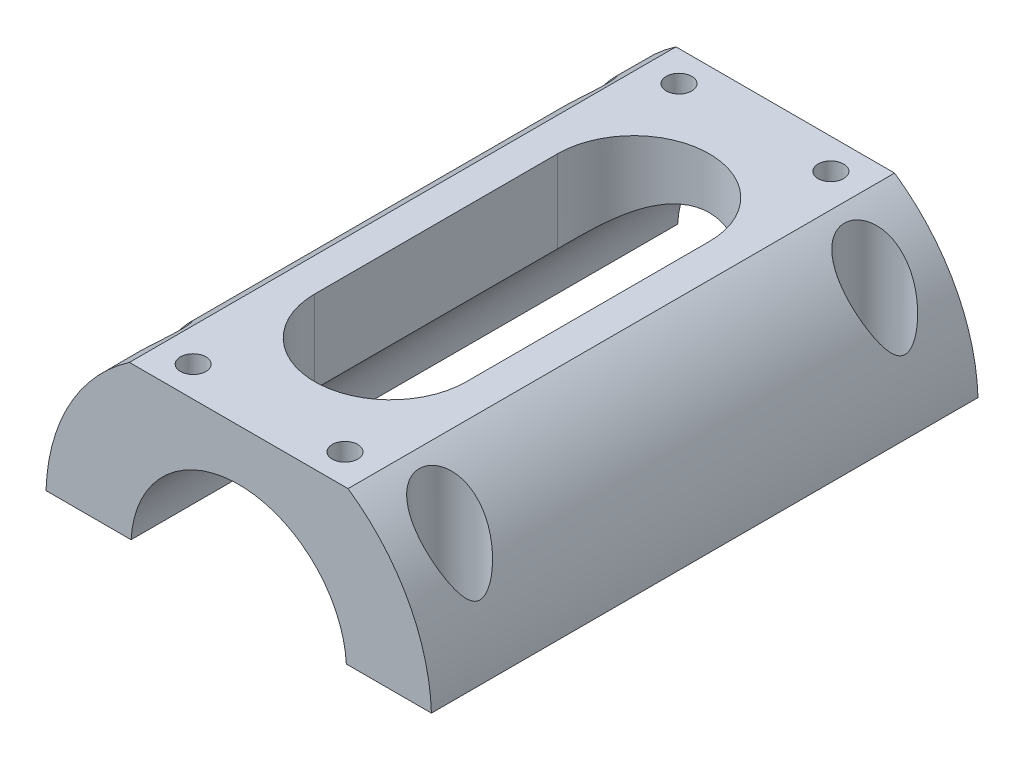
SolidWorks part; units mm, degrees
ref_plane "Front" through (0, 0, 0) normal (0, 0, 1) x (1, 0, 0)
ref_plane "Top" through (0, 0, 0) normal (0, 1, 0) x (1, 0, 0)
ref_plane "Right" through (0, 0, 0) normal (1, 0, 0) x (0, 0, -1)
sketch "Sketch1" plane through (0, 0, 0) normal (0, 0, 1) x (1, 0, 0)
  line L0 (-31.75, 0) -> (31.75, 0) construction
  line L1 (-31.7342, 1) -> (-17.7218, 1)
  line L2 (-31.75, 1) -> (31.75, 1) construction
  line L3 (17.7218, 1) -> (31.7342, 1)
  arc A0 (31.7342, 1) -> (-31.7342, 1) centre (0, 0) ccw
  arc A1 (17.7218, 1) -> (-17.7218, 1) centre (0, 0) ccw
  dimension "D1" = 35.5
  dimension "D2" = 63.5
  dimension "D3" = 1
extrude "Boss-Extrude1" add sketch "Sketch1" along normal blind 90
sketch "Sketch2" plane through (0, 1, 0) normal (0, -1, 0) x (-1, 0, 0)
  line L0 (24.728, -90) -> (24.728, 0) construction
  line L1 (31.7342, -90) -> (17.7218, -90) construction
  line L2 (31.7342, 0) -> (17.7218, 0) construction
  line L3 (-24.728, -90) -> (-24.728, 0) construction
  line L4 (-17.7218, -90) -> (-31.7342, -90) construction
  line L5 (-17.7218, 0) -> (-31.7342, 0) construction
  line L6 (0, -90) -> (0, 0) construction
  line L7 (-17.7218, -90) -> (17.7218, -90) construction
  circle A0 centre (24.728, -80) radius 1
  circle A1 centre (24.728, -10) radius 1
  circle A2 centre (-24.728, -10) radius 1
  circle A3 centre (-24.728, -80) radius 1
  dimension "D1" = 10
  dimension "D2" = 10
  dimension "D3" = 2
hole_wizard "Ø5.0mm Clearance Dowel Hole1" positions "3DSketch1" profile "Sketch3" hole size "Ø5.0" standard "ANSI Metric" end condition up to next
sketch3d "3DSketch1"
  point P0 (-24.728, 1, 80)
  point P3 (-24.728, 1, 10)
  point P6 (24.728, 1, 80)
  point P9 (24.728, 1, 10)
sketch "Sketch3" plane through (-24.728, 1, 80) normal (1, 0, 0) x (0, 0, -1)
  line L0 (0, 0) -> (0, 18.9145)
  line L1 (0, 18.9145) -> (2.5, 18.9145)
  line L2 (2.5, 18.9145) -> (2.5, 0)
  line L5 (2.5, 0) -> (0, 0)
  line L11 (0, -6.35) -> (0, 107.95) construction
  dimension "Thru Hole Dia." = 5
  dimension "Thru Hole Depth" = 18.9145
ref_plane "Plane1" through (0, 4, 0) normal (0, -1, 0) x (-1, 0, 0)
sketch "Sketch4" plane through (0, 4, 0) normal (0, -1, 0) x (-1, 0, 0)
  circle A0 centre (24.728, -80) radius 5
  circle A1 centre (24.728, -10) radius 5
  circle A2 centre (-24.728, -10) radius 5
  circle A3 centre (-24.728, -80) radius 5
  dimension "D1" = 10
extrude "Cut-Extrude1" cut sketch "Sketch4" against normal up to next
sketch "Sketch8" plane through (0, 0, 90) normal (0, 0, 1) x (1, 0, 0)
  line L0 (18, 26.1546) -> (-18, 26.1546)
  arc A0 (31.7342, 1) -> (-31.7342, 1) centre (0, 0) ccw construction
  arc A1 (18, 26.1546) -> (-18, 26.1546) centre (0, 0) ccw
  dimension "D1" = 36
extrude "Cut-Extrude3" cut sketch "Sketch8" against normal through all
sketch "Sketch9" plane through (0, 1, 0) normal (0, -1, 0) x (1, 0, 0)
  line L0 (0, 25) -> (0, 65) construction
  line L1 (0, 90) -> (0, 0) construction
  line L2 (-12.5, 25) -> (-12.5, 65)
  line L3 (12.5, 25) -> (12.5, 65)
  arc A0 (-12.5, 25) -> (12.5, 25) centre (0, 25) ccw
  arc A1 (12.5, 65) -> (-12.5, 65) centre (0, 65) ccw
  point P4 (0, 45)
  dimension "D1" = 25
  dimension "D2" = 40
extrude "Cut-Extrude4" cut sketch "Sketch9" against normal up to next
sketch "Sketch10" plane through (0, 26.1546, 0) normal (0, 1, 0) x (1, 0, 0)
  line L0 (0, -90) -> (0, 0) construction
  line L1 (-12.5, -85) -> (12.5, -85) construction
  line L2 (-12.5, -85) -> (-12.5, -5) construction
  line L3 (-12.5, -5) -> (12.5, -5) construction
  line L4 (12.5, -85) -> (12.5, -5) construction
  line L5 (-12.5, -85) -> (12.5, -5) construction
  line L6 (-12.5, -5) -> (12.5, -85) construction
  circle A0 centre (12.5, -5) radius 2.5
  circle A1 centre (-12.5, -5) radius 2.5
  circle A2 centre (12.5, -85) radius 2.5
  circle A3 centre (-12.5, -85) radius 2.5
  point P0 (0, -45)
  dimension "D1" = 5
  dimension "D2" = 80
  dimension "D3" = 25
hole_wizard "Tap Drill for M5x0.8 Tap1" positions "3DSketch2" profile "Sketch11" hole size "M5x0.8" standard "ANSI Metric"
sketch3d "3DSketch2"
  point P0 (-12.5, 26.1546, 5)
  point P3 (12.5, 26.1546, 5)
  point P6 (12.5, 26.1546, 85)
  point P9 (-12.5, 26.1546, 85)
sketch "Sketch11" plane through (-12.5, 26.1546, 5) normal (1, 0, 0) x (0, 0, 1)
  line L0 (0, 0) -> (0, 9.2618)
  line L1 (0, 9.2618) -> (2.1, 8)
  line L2 (2.1, 8) -> (2.1, 0)
  line L5 (2.1, 0) -> (0, 0)
  line L10 (0, 9.2618) -> (-2.1, 8) construction
  line L11 (0, -6.35) -> (0, 107.95) construction
  dimension "Hole Dia." = 4.2
  dimension "Hole Depth" = 8
  dimension "Drill Angle" = 118
